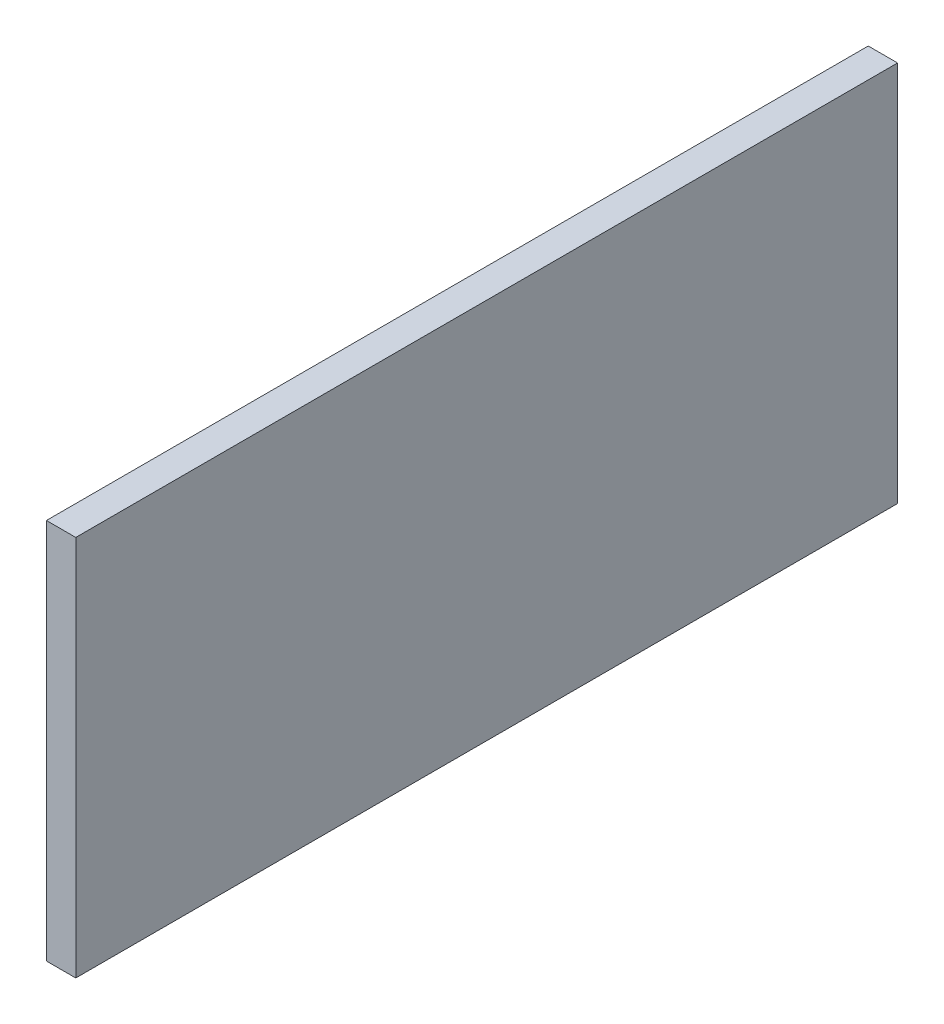
SolidWorks part; units mm, degrees
ref_plane "Front Plane" through (0, 0, 0) normal (0, 0, 1) x (1, 0, 0)
ref_plane "Top Plane" through (0, 0, 0) normal (0, 1, 0) x (1, 0, 0)
ref_plane "Right Plane" through (0, 0, 0) normal (1, 0, 0) x (0, 0, -1)
sketch "Sketch1" plane through (0, 0, 0) normal (1, 0, 0) x (0, 0, -1)
  line L1 (-68.7304, 7.6031) -> (99.2696, 7.6031)
  line L2 (-68.7304, 7.6031) -> (-68.7304, -70.3969)
  line L3 (-68.7304, -70.3969) -> (99.2696, -70.3969)
  line L4 (99.2696, 7.6031) -> (99.2696, -70.3969)
  dimension "D1" = 168
  dimension "D2" = 78
extrude "Boss-Extrude1" add sketch "Sketch1" along normal blind 6
